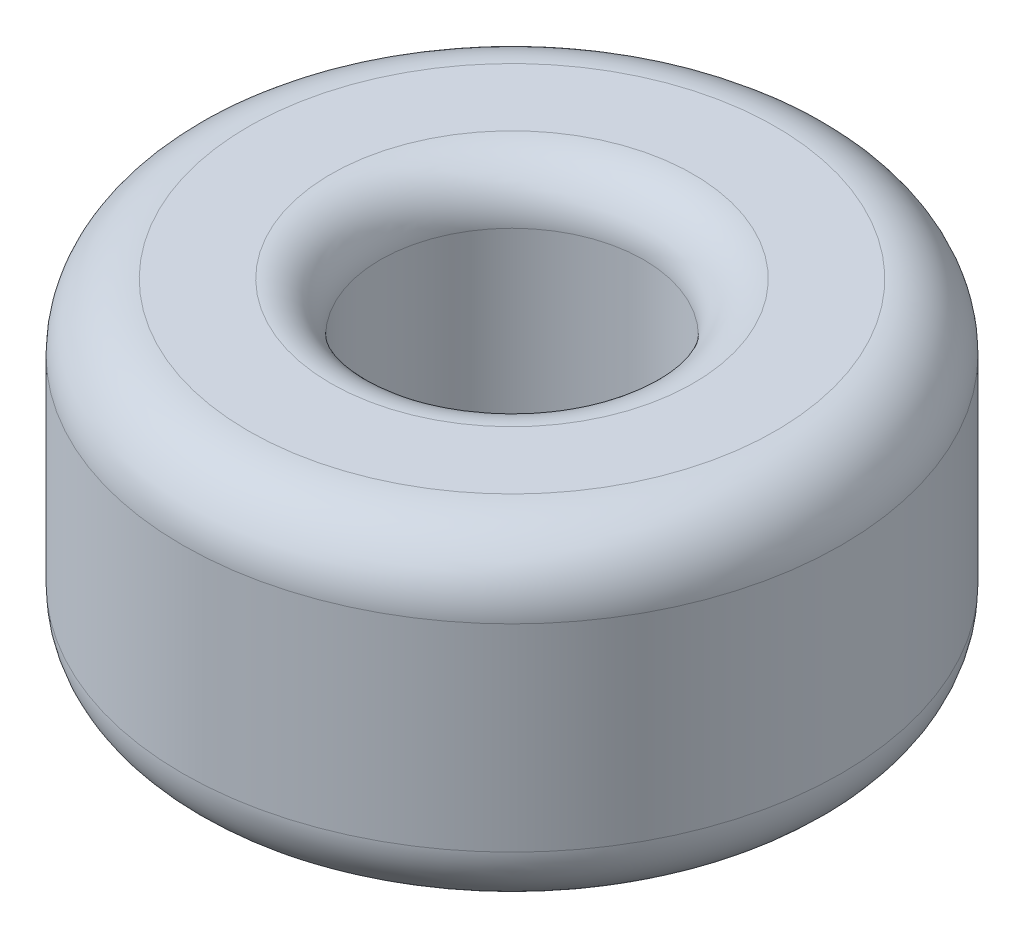
SolidWorks part; units mm, degrees
ref_plane "Alzado" through (0, 0, 0) normal (0, 0, 1) x (1, 0, 0)
ref_plane "Planta" through (0, 0, 0) normal (0, 1, 0) x (1, 0, 0)
ref_plane "Vista lateral" through (0, 0, 0) normal (1, 0, 0) x (0, 0, -1)
sketch "Croquis1" plane through (0, 0, 0) normal (0, 1, 0) x (1, 0, 0)
  circle A0 centre (0, 0) radius 50
  circle A1 centre (0, 0) radius 20
  dimension "D1" = 100
extrude "Saliente-Extruir3" add sketch "Croquis1" along normal blind 50
fillet "Redondeo5" radius 10 2 edges at (0, 0, 50) (0, 50, 50)
fillet "Redondeo6" radius 7.5 2 edges at (0, 50, 20) (0, 0, 20)
